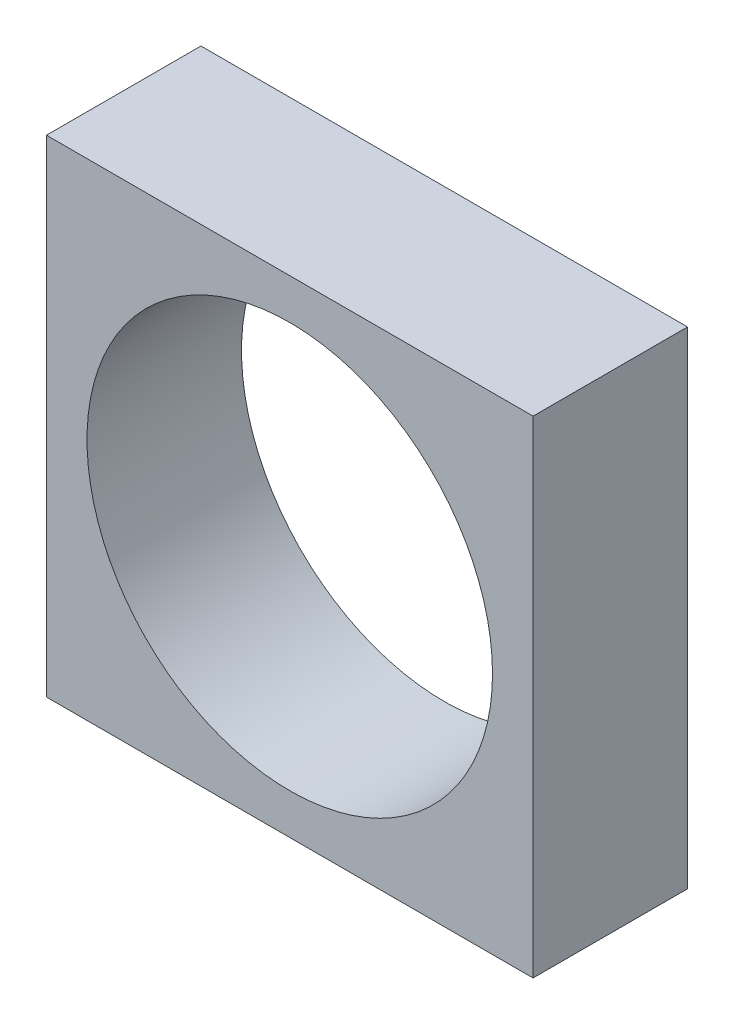
SolidWorks part; units mm, degrees
ref_plane "Front" through (0, 0, 0) normal (0, 0, 1) x (1, 0, 0)
ref_plane "Top" through (0, 0, 0) normal (0, 1, 0) x (1, 0, 0)
ref_plane "Right" through (0, 0, 0) normal (1, 0, 0) x (0, 0, -1)
sketch "Sketch1" plane through (0, 0, 0) normal (0, 0, 1) x (1, 0, 0)
  line L1 (0, 0) -> (60, 0)
  line L2 (0, 0) -> (0, 60)
  line L3 (0, 60) -> (60, 60)
  line L4 (60, 0) -> (60, 60)
  dimension "Xdim" = 60
  dimension "Ydim" = 60
extrude "Boss-Extrude1" add sketch "Sketch1" along normal blind 19.05
sketch "Sketch2" plane through (0, 0, 19.05) normal (0, 0, 1) x (1, 0, 0)
  line L0 (0, 0) -> (60, 60) construction
  circle A0 centre (30, 30) radius 25
  dimension "D1" = 50
extrude "Cut-Extrude1" cut sketch "Sketch2" against normal through all
equation "\"Val1\"= msgbox(\"This equation contains VBA code!\")  'Message Box - only useful for debug"
equation "\"Ydim@Sketch1\"=IIF(\"Xdim@Sketch1\">100, 100, 50) 'IIF function"
equation "\"Zdim@Boss-Extrude1\"=IIF(\"Xdim@Sketch1\">101.6, 19.05, 20) '\"=\" not allowed!"
equation "\"Zdim@Boss-Extrude1\"=IIF(\"Xdim@Sketch1\" Like 101.6, 19.05,20) '\"Like\" instead of \"=\""
equation "\"Zdim@Boss-Extrude1\"=IIF(\"Xdim@Sketch1\">101.6, 20, IIF(\"Xdim@Sketch1\"<101.6, 20,19.05)) 'Nesting IIF Statements"
equation "\"Cut-Extrude1\"=IIF((\"Ydim@Sketch1\"<60) OR (\"Xdim@Sketch1\"<60), \"suppressed\", \"unsuppressed\") 'Logical \"OR\""
